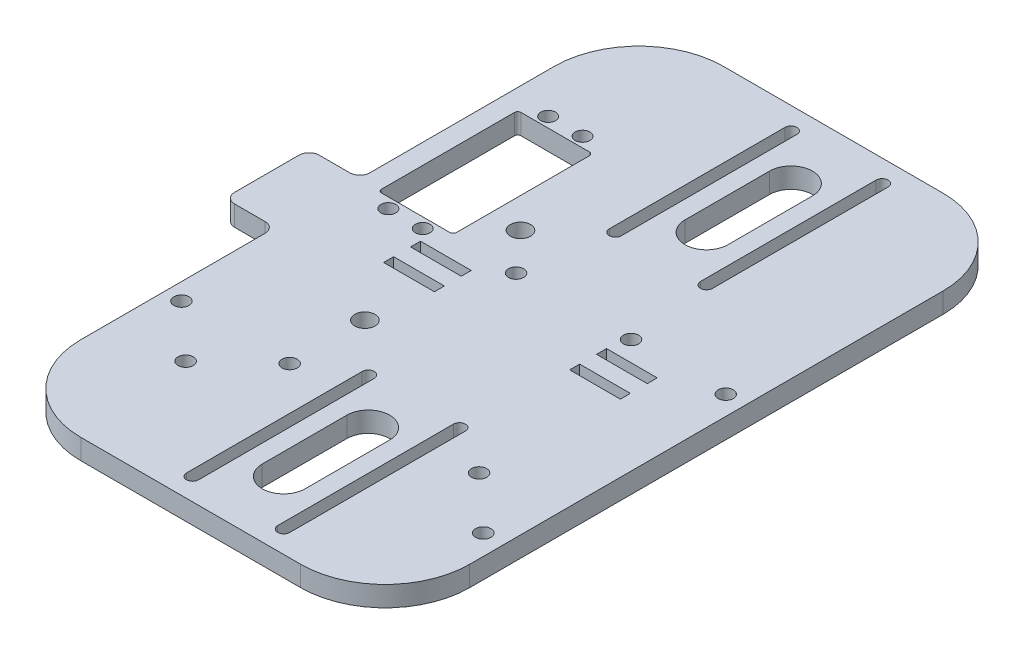
SolidWorks part; units mm, degrees
ref_plane "Plan de face" through (0, 0, 0) normal (0, 0, 1) x (1, 0, 0)
ref_plane "Plan de dessus" through (0, 0, 0) normal (0, 1, 0) x (1, 0, 0)
ref_plane "Plan de droite" through (0, 0, 0) normal (1, 0, 0) x (0, 0, -1)
sketch "Esquisse1" plane through (0, 0, 0) normal (0, 1, 0) x (1, 0, 0)
  line L0 (0, -55) -> (0, 55) construction
  line L1 (-80, -95) -> (50, -95)
  line L2 (-80, -95) -> (-80, 95)
  line L3 (-80, 95) -> (50, 95)
  line L4 (50, -95) -> (50, 95)
  line L5 (-80, -95) -> (50, 95) construction
  line L6 (-80, 95) -> (50, -95) construction
  point P0 (-15, 0)
  dimension "D1" = 190
  dimension "D2" = 130
  dimension "D3" = 50
extrude "Boss.-Extru.1" add sketch "Esquisse1" against normal blind 6 contours L4 L3 L2 L1
sketch "Esquisse2" plane through (0, -6, 0) normal (0, -1, 0) x (1, 0, 0)
  line L0 (13.48, 88.4704) -> (13.48, 36.5296) construction
  line L3 (0, 0) -> (50, 0) construction
  line L4 (50, 95) -> (50, -95) construction
  line L5 (0, 75) -> (0, 50) construction
  line L6 (-6.35, 75) -> (-6.35, 50)
  line L7 (6.35, 75) -> (6.35, 50)
  line L8 (15.258, 88.4704) -> (15.258, 36.5296)
  line L9 (11.702, 88.4704) -> (11.702, 36.5296)
  line L10 (0, -50) -> (0, 50) construction
  line L11 (-13.48, 88.4704) -> (-13.48, 36.5296) construction
  line L12 (-15.258, 88.4704) -> (-15.258, 36.5296)
  line L13 (-11.702, 88.4704) -> (-11.702, 36.5296)
  line L14 (13.48, -88.4704) -> (13.48, -36.5296) construction
  line L15 (15.258, -88.4704) -> (15.258, -36.5296)
  line L16 (11.702, -88.4704) -> (11.702, -36.5296)
  line L17 (0, -75) -> (0, -50) construction
  line L18 (-6.35, -75) -> (-6.35, -50)
  line L19 (6.35, -75) -> (6.35, -50)
  line L20 (-13.48, -88.4704) -> (-13.48, -36.5296) construction
  line L21 (-15.258, -88.4704) -> (-15.258, -36.5296)
  line L22 (-11.702, -88.4704) -> (-11.702, -36.5296)
  line L23 (-80, 95) -> (50, 95) construction
  arc A2 (-15.258, 88.4704) -> (-11.702, 88.4704) centre (-13.48, 88.4704) cw
  arc A3 (-6.35, 75) -> (6.35, 75) centre (0, 75) cw
  arc A4 (6.35, 50) -> (-6.35, 50) centre (0, 50) cw
  arc A5 (-11.702, 36.5296) -> (-15.258, 36.5296) centre (-13.48, 36.5296) cw
  arc A7 (15.258, 88.4704) -> (11.702, 88.4704) centre (13.48, 88.4704) ccw
  arc A8 (11.702, 36.5296) -> (15.258, 36.5296) centre (13.48, 36.5296) ccw
  arc A9 (15.258, -88.4704) -> (11.702, -88.4704) centre (13.48, -88.4704) cw
  arc A10 (11.702, -36.5296) -> (15.258, -36.5296) centre (13.48, -36.5296) cw
  arc A11 (-6.35, -75) -> (6.35, -75) centre (0, -75) ccw
  arc A12 (6.35, -50) -> (-6.35, -50) centre (0, -50) ccw
  arc A13 (-15.258, -88.4704) -> (-11.702, -88.4704) centre (-13.48, -88.4704) ccw
  arc A14 (-11.702, -36.5296) -> (-15.258, -36.5296) centre (-13.48, -36.5296) ccw
  point P3 (13.48, 62.5)
  point P18 (0, 62.5)
  point P26 (-13.48, 62.5)
  point P33 (13.48, -62.5)
  point P39 (0, -62.5)
  point P46 (-13.48, -62.5)
  dimension "D1" = 13.4704
  dimension "D2" = 3.556
  dimension "D3" = 50
  dimension "D4" = 12.7
  dimension "D5" = 13.48
  dimension "D6" = 20
extrude "Enlèv. mat.-Extru.1" cut sketch "Esquisse2" against normal through all
sketch "Esquisse3" plane through (0, -6, 0) normal (0, -1, 0) x (1, 0, 0)
  line L0 (-65, 0) -> (50, 0) construction
  line L1 (50, 95) -> (50, -95) construction
  line L2 (-65, 2.5) -> (50, 2.5) construction
  line L3 (-65, -2.5) -> (50, -2.5) construction
  line L4 (3.3, 0) -> (-3.3, 0) construction
  line L5 (-7.5, 0) -> (79.8014, 0) construction
  line L6 (-40, 2.5) -> (-25, 2.5)
  line L7 (-40, 2.5) -> (-40, 5.45)
  line L8 (-40, 5.45) -> (-25, 5.45)
  line L9 (-25, 2.5) -> (-25, 5.45)
  line L10 (15, 2.5) -> (30, 2.5)
  line L11 (15, 2.5) -> (15, 5.45)
  line L12 (15, 5.45) -> (30, 5.45)
  line L13 (30, 2.5) -> (30, 5.45)
  line L14 (30, -2.5) -> (30, -5.45)
  line L15 (15, -5.45) -> (30, -5.45)
  line L16 (15, -2.5) -> (15, -5.45)
  line L17 (15, -2.5) -> (30, -2.5)
  line L18 (-25, -2.5) -> (-25, -5.45)
  line L19 (-40, -5.45) -> (-25, -5.45)
  line L20 (-40, -2.5) -> (-40, -5.45)
  line L21 (-40, -2.5) -> (-25, -2.5)
  line L23 (-53.085, -9.02) -> (-42.915, -9.02) construction
  line L24 (-53.085, -9.02) -> (-53.085, -56.28) construction
  line L25 (-53.085, -56.28) -> (-42.915, -56.28) construction
  line L26 (-42.915, -9.02) -> (-42.915, -56.28) construction
  arc A0 (-65, 2.5) -> (-65, -2.5) centre (-65, 0) ccw construction
  arc A1 (50, -2.5) -> (50, 2.5) centre (50, 0) ccw construction
  circle A4 centre (-53.085, -9.02) radius 2.19
  circle A7 centre (-42.915, -56.28) radius 2.19
  circle A9 centre (-53.085, -56.28) radius 2.19
  circle A10 centre (-42.915, -9.02) radius 2.19
  point P4 (-7.5, 0)
  point P19 (30, 3.975)
  dimension "D9" = 9.02
  dimension "D10" = 47.26
  dimension "D13" = 4.38
  dimension "D1" = 5
  dimension "D2" = 115
  dimension "D3" = 15
  dimension "D4" = 2.95
  dimension "D5" = 2.95
  dimension "D6" = 15
  dimension "D7" = 40
  dimension "D8" = 20
  dimension "D11" = 10.17
  dimension "D12" = 42.915
extrude "Enlèv. mat.-Extru.2" cut sketch "Esquisse3" against normal through all
sketch "Esquisse5" plane through (0, -6, 0) normal (0, -1, 0) x (1, 0, 0)
  line L0 (-47.9186, 11.5) -> (-28, 23) construction
  line L1 (-28, 23) -> (-28, -23) construction
  line L2 (-28, -23) -> (-47.9186, -11.5) construction
  line L3 (-47.9186, -11.5) -> (-47.9186, 11.5) construction
  line L4 (0, 0) -> (-102.417, 0) construction
  line L5 (3.3, 0) -> (-3.3, 0) construction
  circle A0 centre (-28, 23) radius 3
  circle A1 centre (-47.9186, 11.5) radius 3 construction
  circle A2 centre (-47.9186, -11.5) radius 3 construction
  circle A3 centre (-28, -23) radius 3
  circle A4 centre (-28, 0) radius 20 construction
  dimension "D1" = 6
  dimension "D2" = 6
  dimension "D4" = 6
  dimension "D5" = 40
  dimension "D3" = 28
extrude "Enlèv. mat.-Extru.3" cut sketch "Esquisse5" against normal through all
sketch "Sketch1" plane through (0, -6, 0) normal (0, -1, 0) x (1, 0, 0)
  line L1 (-53.085, -56.28) -> (-42.915, -56.28) construction
  line L2 (-53.085, -56.28) -> (-53.085, -9.02) construction
  line L3 (-53.085, -9.02) -> (-42.915, -9.02) construction
  line L4 (-42.915, -56.28) -> (-42.915, -9.02) construction
  line L5 (-59.085, -53.28) -> (-36.915, -53.28)
  line L6 (-59.085, -53.28) -> (-59.085, -12.02)
  line L7 (-59.085, -12.02) -> (-36.915, -12.02)
  line L8 (-36.915, -53.28) -> (-36.915, -12.02)
  point P10 (-53.085, -32.65)
  dimension "D4" = 6
  dimension "D1" = 3
  dimension "D2" = 3
  dimension "D3" = 6
extrude "Cut-Extrude1" cut sketch "Sketch1" against normal up to next
fillet "Fillet1" radius 1
hole_wizard "M4 Clearance Hole1" positions "Sketch2" profile "Sketch4" hole size "M4" standard "ANSI Metric"
sketch "Sketch2" plane through (0, -6, 0) normal (0, -1, 0) x (-1, 0, 0)
  point P0 (-28, -45.2375)
  point P3 (-44, -60)
  point P6 (28, -45.2375)
  point P9 (44, -60)
  point P12 (60, -45.2375)
sketch "Sketch4" plane through (28, -6, 45.2375) normal (1, 0, 0) x (0, 0, -1)
  line L0 (0, 0) -> (0, 6)
  line L1 (0, 6) -> (2.25, 6)
  line L2 (2.25, 6) -> (2.25, 0)
  line L5 (2.25, 0) -> (0, 0)
  line L11 (0, -6.35) -> (0, 107.95) construction
  dimension "Thru Hole Dia." = 4.5
  dimension "Thru Hole Depth" = 6
sketch "Sketch5" plane through (0, -6, 0) normal (0, -1, 0) x (1, 0, 0)
  line L0 (-80, 95) -> (50, 95) construction
  line L1 (-65, 95) -> (-80, 95)
  line L2 (-65, 95) -> (-65, -95)
  line L3 (-65, -95) -> (-80, -95)
  line L4 (-80, 95) -> (-80, -95)
  line L5 (-80, -95) -> (50, -95) construction
  line L6 (-80, 95) -> (-80, -95) construction
  line L7 (0, 0) -> (-80, 0) construction
  line L8 (-80, 12.5) -> (-65, 12.5)
  line L9 (-80, 12.5) -> (-80, -12.5)
  line L10 (-80, -12.5) -> (-65, -12.5)
  line L11 (-65, 12.5) -> (-65, -12.5)
  point P10 (-65, 0)
  point P11 (-80, 0)
  point P20 (-72.5, 12.5)
  dimension "D1" = 15
  dimension "D2" = 25
extrude "Cut-Extrude2" cut sketch "Sketch5" against normal up to next contours L4 L8 L2 L1 | L10 L4 L3 L2
fillet "Fillet2" radius 25
fillet "Fillet3" radius 3
hole_wizard "#8 Clearance Hole1" positions "Sketch8" profile "Sketch9" hole size "#8" standard "ANSI Inch" end condition up to next
sketch "Sketch8" plane through (0, 0, 0) normal (0, 1, 0) x (1, 0, 0)
  point P4 (16.3, 11.3944)
  point P7 (-17.7, 11.3944)
  point P14 (44.3, 11.3944)
sketch "Sketch9" plane through (16.3, 0, -11.3944) normal (1, 0, 0) x (0, 0, 1)
  line L0 (0, 0) -> (0, 6)
  line L1 (0, 6) -> (2.2479, 6)
  line L2 (2.2479, 6) -> (2.2479, 0)
  line L5 (2.2479, 0) -> (0, 0)
  line L11 (0, -6.35) -> (0, 107.95) construction
  dimension "Thru Hole Dia." = 4.4958
  dimension "Thru Hole Depth" = 6
equation "\"D4@Esquisse5\"=\"D1@Esquisse5\""
equation "\"D2@Esquisse5\"=\"D1@Esquisse5\""
equation "\"D4@Sketch1\"=\"D3@Sketch1\""
